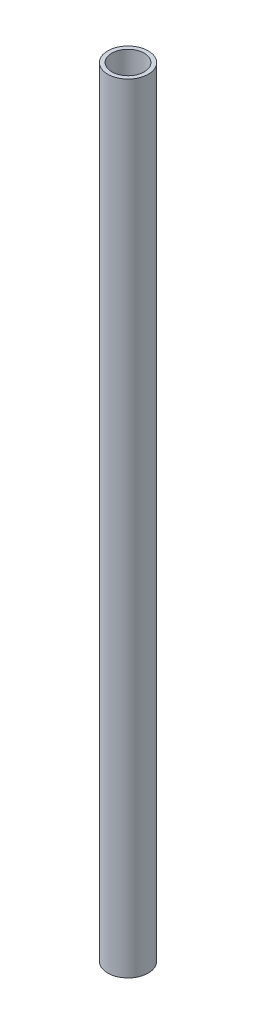
SolidWorks part; units mm, degrees
material "Plain Carbon Steel"
ref_plane "Front Plane" through (0, 0, 0) normal (0, 0, 1) x (1, 0, 0)
ref_plane "Top Plane" through (0, 0, 0) normal (0, 1, 0) x (1, 0, 0)
ref_plane "Right Plane" through (0, 0, 0) normal (1, 0, 0) x (0, 0, -1)
sketch "Sketch1" plane through (0, 0, 0) normal (0, 1, 0) x (1, 0, 0)
  circle A0 centre (0, 0) radius 15.875
  circle A1 centre (0, 0) radius 12.7
  dimension "D1" = 31.75
  dimension "D2" = 25.4
extrude "Shaft extrusion" add sketch "Sketch1" along normal blind 609.6
